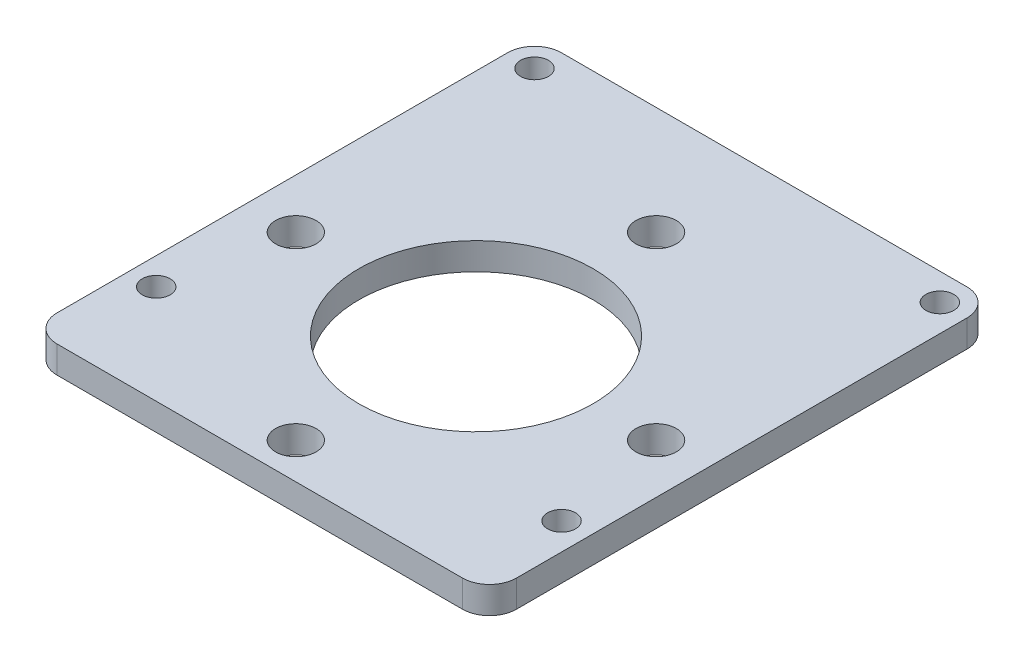
SolidWorks part; units mm, degrees
ref_plane "Front Plane" through (0, 0, 0) normal (0, 0, 1) x (1, 0, 0)
ref_plane "Top Plane" through (0, 0, 0) normal (0, 1, 0) x (1, 0, 0)
ref_plane "Right Plane" through (0, 0, 0) normal (1, 0, 0) x (0, 0, -1)
sketch "Sketch1" plane through (0, 0, 0) normal (0, 1, 0) x (1, 0, 0)
  line L0 (-24.6213, 23.1213) -> (-22.5, 21) construction
  line L1 (22.5, -24) -> (-22.5, -24)
  line L2 (25.5, -21) -> (25.5, 21)
  line L3 (22.5, 24) -> (-22.5, 24)
  line L4 (-25.5, -21) -> (-25.5, 21)
  line L5 (25.5, -24) -> (-25.5, 24) construction
  line L6 (25.5, 24) -> (-25.5, -24) construction
  line L7 (0, -50) -> (0, 50) construction
  line L8 (50, 0) -> (-50, 0) construction
  line L9 (0, 24) -> (0, -8) construction
  line L11 (-25.5, -21) -> (25.5, -21)
  line L12 (-25.5, -21) -> (-25.5, -29)
  line L13 (-22.5, -32) -> (22.5, -32)
  line L14 (25.5, -21) -> (25.5, -29)
  arc A0 (-22.5, -24) -> (-25.5, -21) centre (-22.5, -21) cw
  arc A1 (22.5, -24) -> (25.5, -21) centre (22.5, -21) ccw
  arc A2 (25.5, 21) -> (22.5, 24) centre (22.5, 21) ccw
  arc A3 (-22.5, 24) -> (-25.5, 21) centre (-22.5, 21) ccw
  circle A4 centre (-22.5, 21) radius 1.55
  circle A5 centre (-22.5, -21) radius 1.55
  circle A6 centre (22.5, -21) radius 1.55
  circle A7 centre (22.5, 21) radius 1.55
  circle A8 centre (0, 0) radius 12.5 construction
  circle A9 centre (0, 12.5) radius 1.75 construction
  circle A10 centre (0, -12.5) radius 1.75 construction
  circle A13 centre (0, 0) radius 7 construction
  circle A14 centre (-12.5, 0) radius 1.75 construction
  circle A15 centre (12.5, 0) radius 1.75 construction
  circle A16 centre (0, -8) radius 20 construction
  circle A17 centre (0, 12) radius 2.25
  circle A19 centre (0, -8) radius 13
  circle A20 centre (-20, -8) radius 2.25
  circle A21 centre (20, -8) radius 2.25
  circle A22 centre (0, -28) radius 2.25
  arc A23 (22.5, -32) -> (25.5, -29) centre (22.5, -29) ccw
  arc A24 (-25.5, -29) -> (-22.5, -32) centre (-22.5, -29) ccw
  point P1 (0, 0)
  point P23 (0, 0)
  point P26 (0, 0)
  dimension "D3" = 3
  dimension "D4" = 32
  dimension "D6" = 8
  dimension "D7" = 3
  dimension "D8" = 26
  dimension "D1" = 51
  dimension "D2" = 48
  dimension "D5" = 0
extrude "Motor_Plate" add sketch "Sketch1" along normal blind 3 contours L12 A24 L13 A23 L14 A1 L1 A0 A22 | A6 L11 L2 A2 L3 A3 L4 A5 A21 A20 A19 A17 A4 A7 | A6 L11 A5 A0 L1 A1
